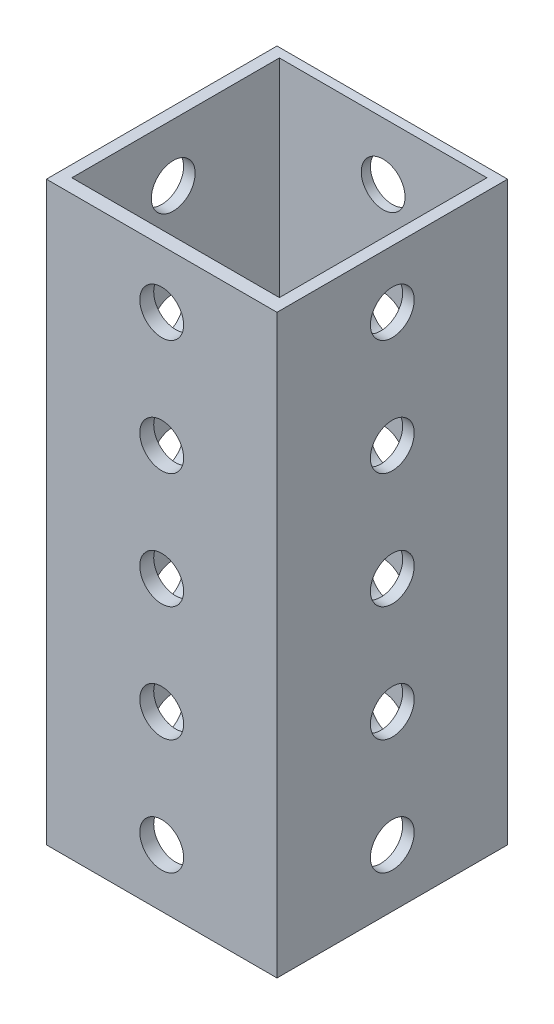
SolidWorks part; units mm, degrees
ref_plane "Front Plane" through (0, 0, 0) normal (0, 0, 1) x (1, 0, 0)
ref_plane "Top Plane" through (0, 0, 0) normal (0, 1, 0) x (1, 0, 0)
ref_plane "Right Plane" through (0, 0, 0) normal (1, 0, 0) x (0, 0, -1)
sketch "Sketch2" plane through (0, 0, 0) normal (0, 1, 0) x (1, 0, 0)
  line L1 (-12.7, -12.7) -> (12.7, -12.7)
  line L2 (-12.7, -12.7) -> (-12.7, 12.7)
  line L3 (-12.7, 12.7) -> (12.7, 12.7)
  line L4 (12.7, -12.7) -> (12.7, 12.7)
  line L7 (-11.43, -11.1675) -> (11.43, -11.1675)
  line L8 (-11.43, -11.1675) -> (-11.43, 11.6925)
  line L9 (-11.43, 11.6925) -> (11.43, 11.6925)
  line L10 (11.43, -11.1675) -> (11.43, 11.6925)
  point P0 (0, 0)
  point P6 (0, 0)
  dimension "D1" = 25.4
  dimension "D2" = 25.4
  dimension "D3" = 22.86
extrude "Boss-Extrude1" add sketch "Sketch2" along normal blind 63.5
sketch "Sketch3" plane through (0, 0, -12.7) normal (0, 0, -1) x (-1, 0, 0)
  line L0 (0, 63.5) -> (0, 0) construction
  line L1 (-12.7, 63.5) -> (12.7, 63.5) construction
  circle A0 centre (0, 57.15) radius 2.413
  circle A1 centre (0, 44.45) radius 2.413
  circle A2 centre (0, 31.75) radius 2.413
  circle A3 centre (0, 19.05) radius 2.413
  circle A4 centre (0, 6.35) radius 2.413
  circle A5 centre (0, -6.35) radius 2.413
  dimension "D1" = 4.826
  dimension "D2" = 6.35
  dimension "D3" = 6
extrude "Cut-Extrude1" cut sketch "Sketch3" against normal through all
sketch "Sketch4" plane through (12.7, 0, 0) normal (1, 0, 0) x (0, 0, -1)
  line L0 (0, 63.5) -> (0, 0) construction
  line L1 (-12.7, 63.5) -> (12.7, 63.5) construction
  circle A0 centre (0, 57.15) radius 2.413
  circle A1 centre (0, 44.45) radius 2.413
  circle A2 centre (0, 31.75) radius 2.413
  circle A3 centre (0, 19.05) radius 2.413
  circle A4 centre (0, 6.35) radius 2.413
  circle A5 centre (0, -6.35) radius 2.413
  dimension "D1" = 4.826
  dimension "D2" = 6.35
  dimension "D3" = 6
extrude "Cut-Extrude2" cut sketch "Sketch4" against normal through all
